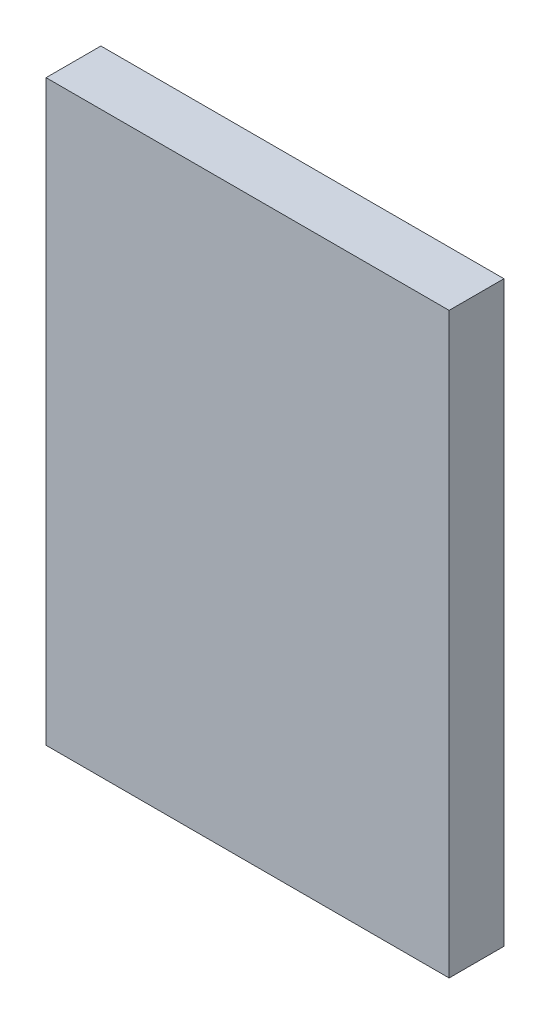
SolidWorks part; units mm, degrees
ref_plane "Спереди" through (0, 0, 0) normal (0, 0, 1) x (1, 0, 0)
ref_plane "Сверху" through (0, 0, 0) normal (0, 1, 0) x (1, 0, 0)
ref_plane "Справа" through (0, 0, 0) normal (1, 0, 0) x (0, 0, -1)
other "Configuration Table"
sketch "Эскиз1" plane through (0, 0, 0) normal (0, 0, 1) x (1, 0, 0)
  line L1 (-34.925, -58.2) -> (34.925, -58.2)
  line L2 (-34.925, -58.2) -> (-34.925, 42)
  line L3 (-34.925, 42) -> (34.925, 42)
  line L4 (34.925, -58.2) -> (34.925, 42)
extrude "HDD_69_85x100_2x9_5_1" add sketch "Эскиз1" along normal blind 9.5
